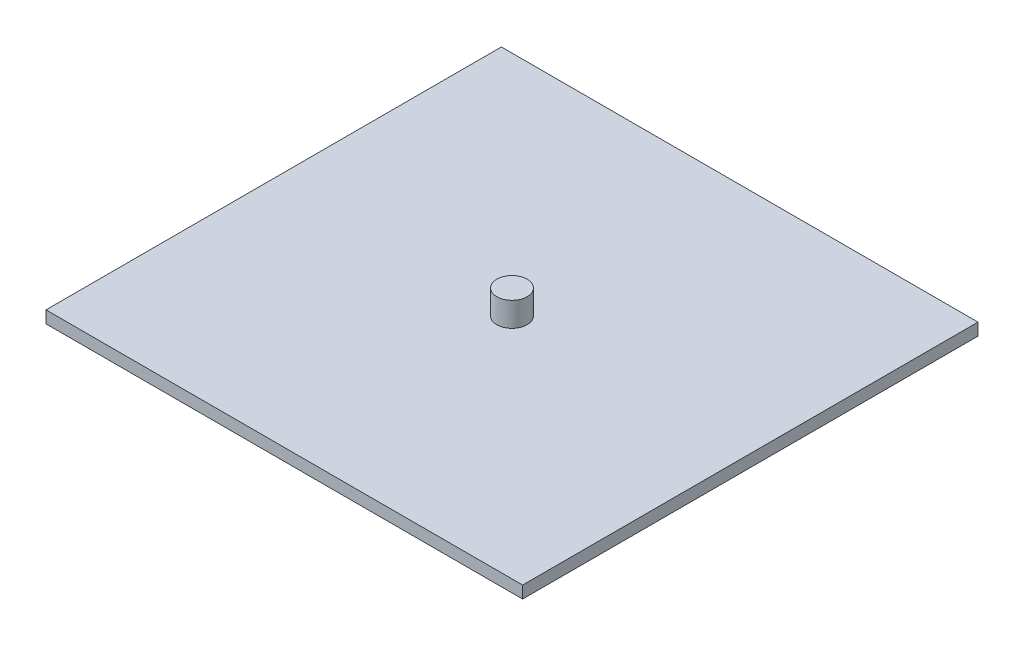
SolidWorks part; units mm, degrees
ref_plane "Alzado" through (0, 0, 0) normal (0, 0, 1) x (1, 0, 0)
ref_plane "Planta" through (0, 0, 0) normal (0, 1, 0) x (1, 0, 0)
ref_plane "Vista lateral" through (0, 0, 0) normal (1, 0, 0) x (0, 0, -1)
sketch "Croquis1" plane through (0, 0, 0) normal (0, 1, 0) x (1, 0, 0)
  line L1 (-39.25, -37.5) -> (39.25, -37.5)
  line L2 (-39.25, -37.5) -> (-39.25, 37.5)
  line L3 (-39.25, 37.5) -> (39.25, 37.5)
  line L4 (39.25, -37.5) -> (39.25, 37.5)
  line L5 (-39.25, -37.5) -> (39.25, 37.5) construction
  line L6 (-39.25, 37.5) -> (39.25, -37.5) construction
  point P0 (0, 0)
  dimension "D1" = 78.5
  dimension "D2" = 75
extrude "Saliente-Extruir1" add sketch "Croquis1" along normal blind 2
sketch "Croquis2" plane through (0, 2, 0) normal (0, 1, 0) x (1, 0, 0)
  circle A0 centre (0, 0) radius 2.5
  dimension "D1" = 5
extrude "Saliente-Extruir2" add sketch "Croquis2" along normal blind 4
